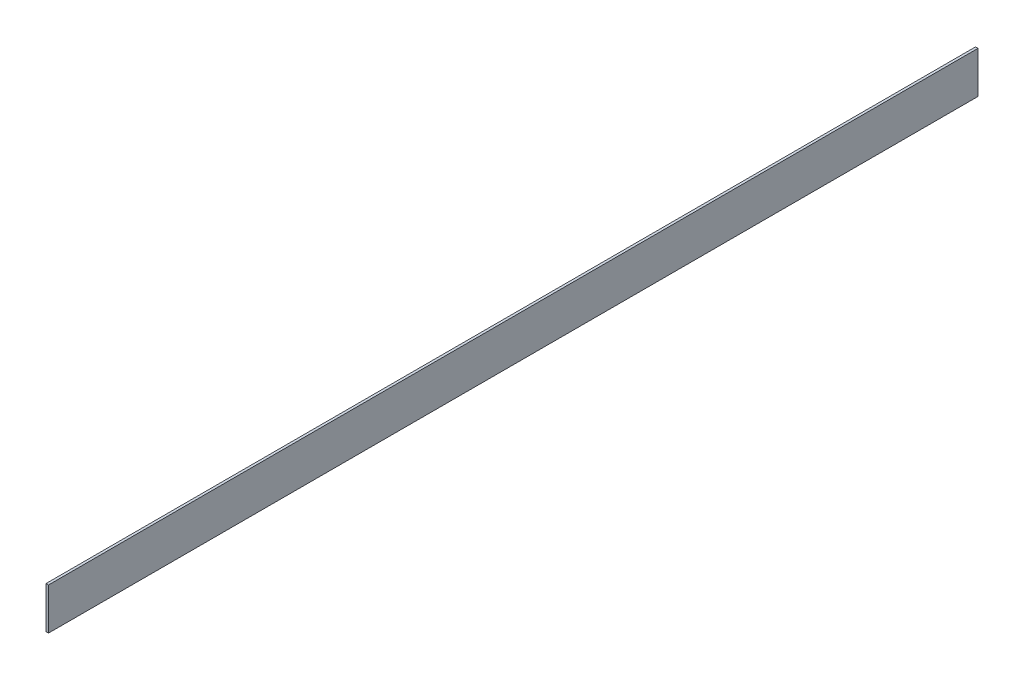
SolidWorks part; units mm, degrees
ref_plane "Front Plane" through (0, 0, 0) normal (0, 0, 1) x (1, 0, 0)
ref_plane "Top Plane" through (0, 0, 0) normal (0, 1, 0) x (1, 0, 0)
ref_plane "Right Plane" through (0, 0, 0) normal (1, 0, 0) x (0, 0, -1)
sketch "Sketch1" plane through (0, 0, 0) normal (0, 0, 1) x (1, 0, 0)
  line L1 (0, 0) -> (3.175, 0)
  line L2 (0, 0) -> (0, 53.34)
  line L3 (0, 53.34) -> (3.175, 53.34)
  line L4 (3.175, 0) -> (3.175, 53.34)
  dimension "D1" = 3.175
  dimension "D2" = 53.34
extrude "Boss-Extrude1" add sketch "Sketch1" along normal blind 1188.466
